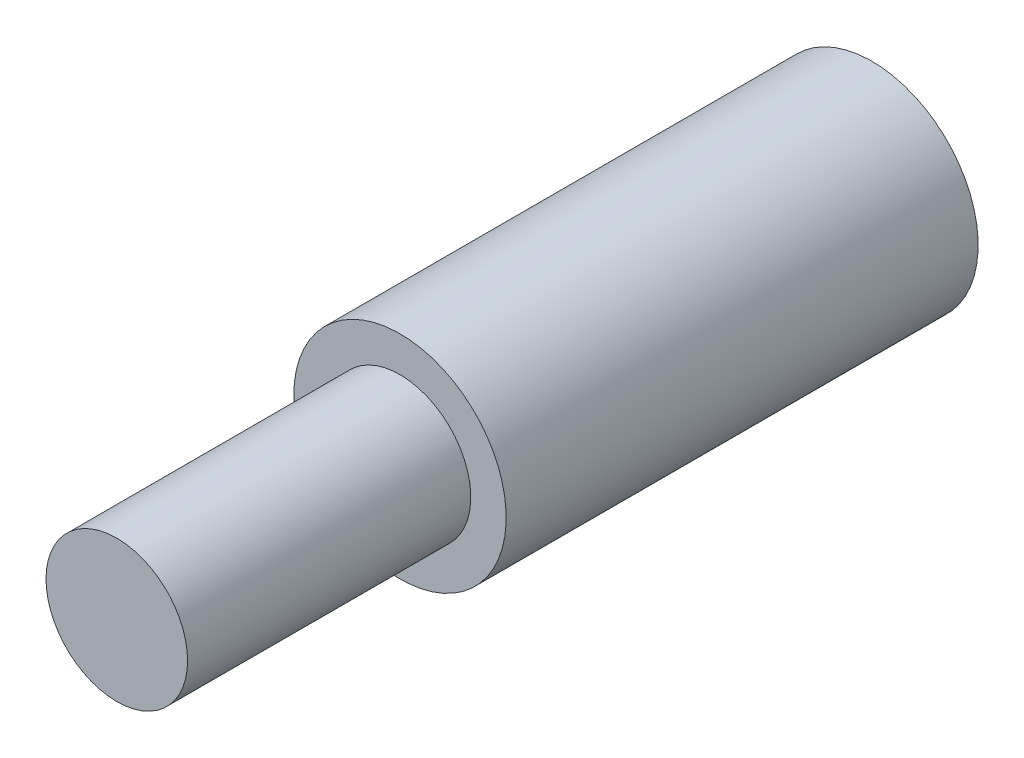
SolidWorks part; units mm, degrees
material "Aluminum"
ref_plane "Front Plane" through (0, 0, 0) normal (0, 0, 1) x (1, 0, 0)
ref_plane "Top Plane" through (0, 0, 0) normal (0, 1, 0) x (1, 0, 0)
ref_plane "Right Plane" through (0, 0, 0) normal (1, 0, 0) x (0, 0, -1)
sketch "Sketch1" plane through (0, 0, 0) normal (0, 0, 1) x (1, 0, 0)
  circle A0 centre (0, 0) radius 1.5
  dimension "D1" = 3
extrude "Boss-Extrude1" add sketch "Sketch1" along normal blind 6
sketch "Sketch2" plane through (0, 0, 0) normal (0, 0, -1) x (-1, 0, 0)
  circle A0 centre (0, 0) radius 2.25
  dimension "D1" = 4.5
extrude "Boss-Extrude2" add sketch "Sketch2" along normal blind 10
sketch "Sketch3" plane through (0, 0, -10) normal (0, 0, -1) x (-1, 0, 0)
  circle A0 centre (0, 0) radius 1.5
  dimension "D1" = 3
extrude "Cut-Extrude1" cut sketch "Sketch3" against normal blind 4
